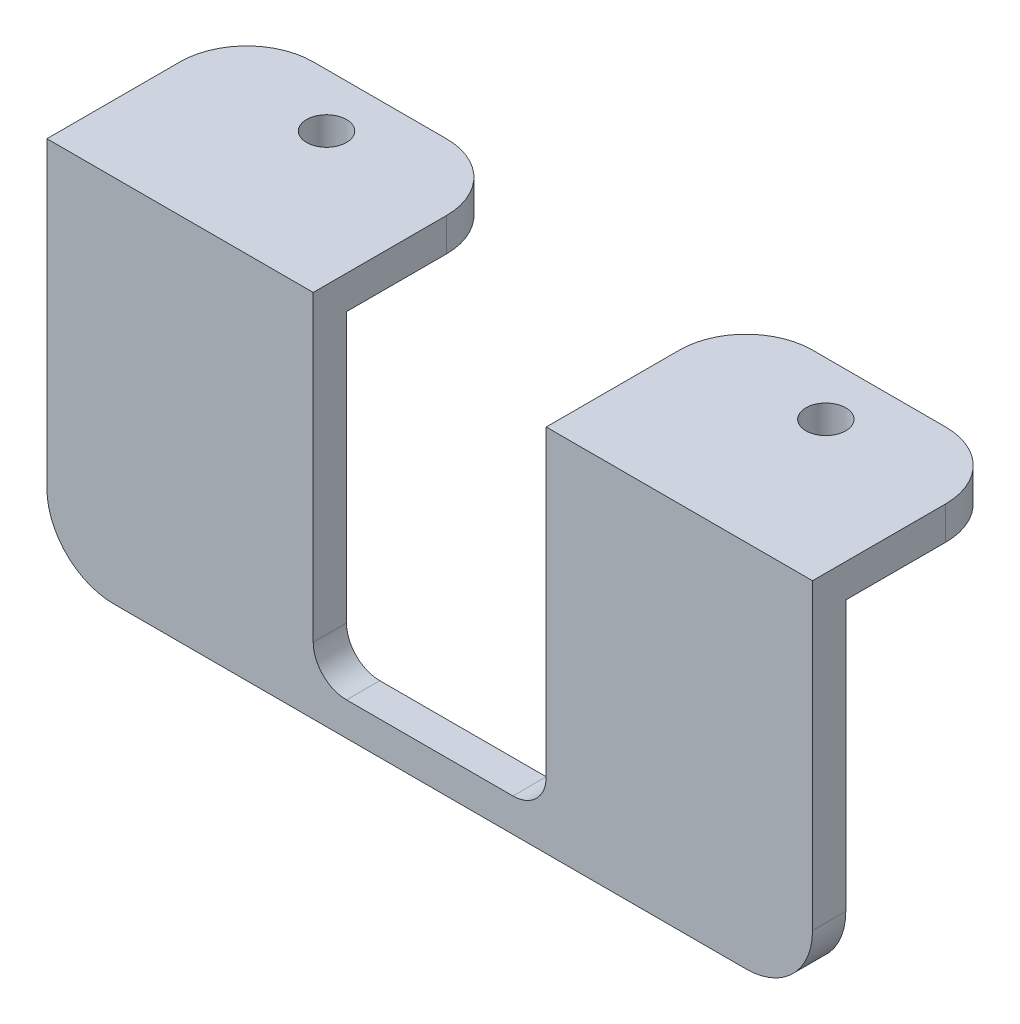
SolidWorks part; units mm, degrees
ref_plane "Front Plane" through (0, 0, 0) normal (0, 0, 1) x (1, 0, 0)
ref_plane "Top Plane" through (0, 0, 0) normal (0, 1, 0) x (1, 0, 0)
ref_plane "Right Plane" through (0, 0, 0) normal (1, 0, 0) x (0, 0, -1)
sketch "Sketch1" plane through (0, 0, 0) normal (0, 1, 0) x (1, 0, 0)
  line L1 (17.5, 30) -> (57.5, 30)
  line L2 (17.5, 30) -> (17.5, 0)
  line L3 (17.5, 0) -> (57.5, 0)
  line L4 (57.5, 30) -> (57.5, 0)
  point P7 (8.3992, -3.3482)
  dimension "D1" = 40
  dimension "D2" = 30
  dimension "D3" = 0
  dimension "D4" = 17.5
extrude "Boss-Extrude1" add sketch "Sketch1" along normal blind 5
sketch "Sketch2" plane through (0, 0, 0) normal (0, -1, 0) x (1, 0, 0)
  line L0 (57.5, 0) -> (57.5, -30) construction
  line L1 (17.5, 0) -> (57.5, 0)
  line L2 (17.5, 0) -> (17.5, -5)
  line L3 (17.5, -5) -> (57.5, -5)
  line L4 (57.5, 0) -> (57.5, -5)
  dimension "D1" = 5
extrude "Boss-Extrude2" add sketch "Sketch2" along normal blind 45.5
sketch "Sketch3" plane through (0, -45.5, 0) normal (0, -1, 0) x (1, 0, 0)
  line L1 (57.5, -5) -> (0, -5)
  line L2 (57.5, -5) -> (57.5, 0)
  line L3 (57.5, 0) -> (0, 0)
  line L4 (0, -5) -> (0, 0)
extrude "Boss-Extrude3" add sketch "Sketch3" along normal blind 5
fillet "Fillet1" radius 10 1 edges at (57.5, -50.5, -2.5)
fillet "Fillet2" radius 5 1 edges at (17.5, -45.5, -2.5)
fillet "Fillet3" radius 10 2 edges at (57.5, 2.5, -30) (17.5, 2.5, -30)
sketch "Sketch4" plane through (0, 5, 0) normal (0, 1, 0) x (1, 0, 0)
  line L0 (17.5, 20) -> (17.5, 0) construction
  line L2 (47.5, 30) -> (27.5, 30) construction
  circle A0 centre (37.5, 22) radius 3
  dimension "D3" = 6
  dimension "D1" = 20
  dimension "D2" = 8
extrude "Cut-Extrude1" cut sketch "Sketch4" against normal through all contours A0
mirror "Mirror1" about plane through (0, 0, 0) normal (1, 0, 0) of bodies 104
